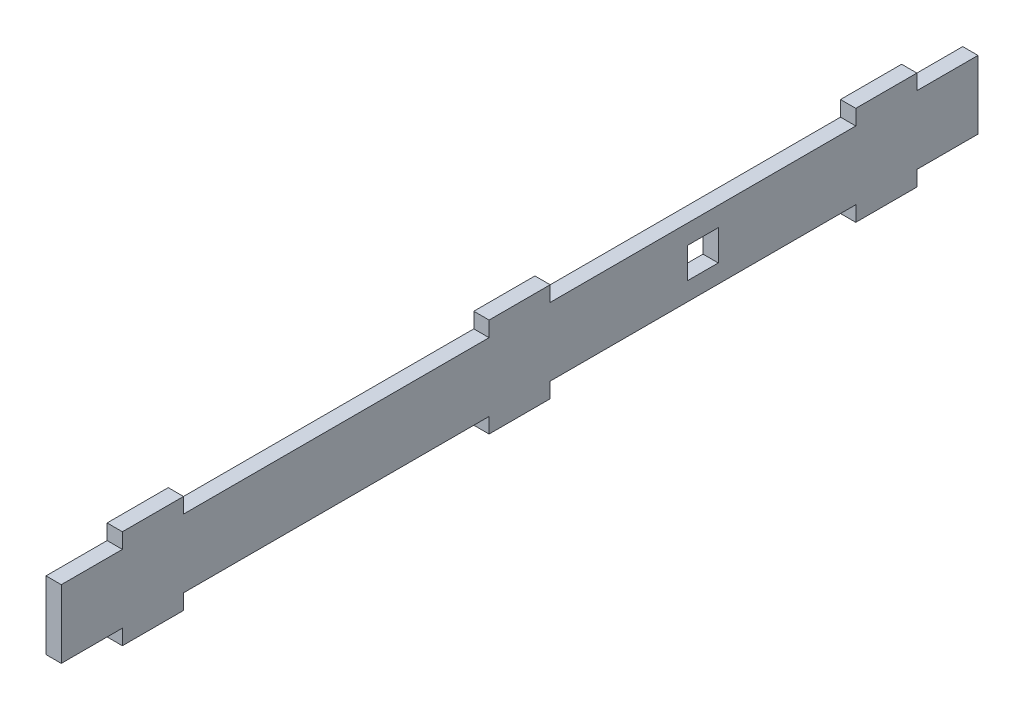
SolidWorks part; units mm, degrees
ref_plane "Front Plane" through (0, 0, 0) normal (0, 0, 1) x (1, 0, 0)
ref_plane "Top Plane" through (0, 0, 0) normal (0, 1, 0) x (1, 0, 0)
ref_plane "Right Plane" through (0, 0, 0) normal (1, 0, 0) x (0, 0, -1)
sketch "Sketch1" plane through (0, 0, 0) normal (1, 0, 0) x (0, 0, -1)
  line L1 (0, 0) -> (300, 0)
  line L2 (0, 0) -> (0, 22.32)
  line L3 (0, 22.32) -> (300, 22.32)
  line L4 (300, 0) -> (300, 22.32)
  dimension "D1" = 22.32
  dimension "D2" = 300
extrude "Boss-Extrude1" add sketch "Sketch1" along normal blind 5
sketch "Sketch2" plane through (0, 22.32, 0) normal (0, 1, 0) x (1, 0, 0)
  line L0 (0, 300) -> (0, 0) construction
  line L1 (0, 20) -> (5, 20)
  line L2 (0, 20) -> (0, 40)
  line L3 (0, 40) -> (5, 40)
  line L4 (5, 20) -> (5, 40)
  line L5 (5, 300) -> (5, 0) construction
  line L6 (5, 0) -> (0, 0) construction
  line L7 (0, 280) -> (5, 280)
  line L8 (0, 280) -> (0, 260)
  line L9 (0, 260) -> (5, 260)
  line L10 (5, 280) -> (5, 260)
  line L11 (0, 160) -> (5, 160)
  line L12 (0, 160) -> (0, 140)
  line L13 (0, 140) -> (5, 140)
  line L14 (5, 160) -> (5, 140)
  line L15 (5, 300) -> (0, 300) construction
  dimension "D1" = 20
  dimension "D2" = 20
  dimension "D3" = 20
  dimension "D4" = 140
  dimension "D5" = 20
  dimension "D6" = 20
extrude "Boss-Extrude2" add sketch "Sketch2" along normal blind 5
sketch "Sketch3" plane through (0, 0, 0) normal (0, -1, 0) x (1, 0, 0)
  line L0 (5, 0) -> (5, -300) construction
  line L1 (5, -20) -> (0, -20)
  line L2 (5, -20) -> (5, -40)
  line L3 (5, -40) -> (0, -40)
  line L4 (0, -20) -> (0, -40)
  line L5 (0, 0) -> (0, -300) construction
  line L6 (5, 0) -> (0, 0) construction
  line L7 (5, -140) -> (0, -140)
  line L8 (5, -140) -> (5, -160)
  line L9 (5, -160) -> (0, -160)
  line L10 (0, -140) -> (0, -160)
  line L11 (5, -260) -> (0, -260)
  line L12 (5, -260) -> (5, -280)
  line L13 (5, -280) -> (0, -280)
  line L14 (0, -260) -> (0, -280)
  line L15 (5, -300) -> (0, -300) construction
  dimension "D1" = 20
  dimension "D2" = 20
  dimension "D3" = 20
  dimension "D4" = 140
  dimension "D5" = 20
  dimension "D6" = 20
extrude "Boss-Extrude3" add sketch "Sketch3" along normal blind 5
sketch "Sketch4" plane through (5, 0, 0) normal (1, 0, 0) x (0, 0, -1)
  line L0 (300, 0) -> (300, 22.32) construction
  line L1 (215, 16) -> (205, 16)
  line L2 (215, 16) -> (215, 6)
  line L3 (215, 6) -> (205, 6)
  line L4 (205, 16) -> (205, 6)
  line L5 (160, 0) -> (260, 0) construction
  dimension "D1" = 10
  dimension "D2" = 10
  dimension "D3" = 85
  dimension "D4" = 6
extrude "Cut-Extrude1" cut sketch "Sketch4" against normal blind 5
